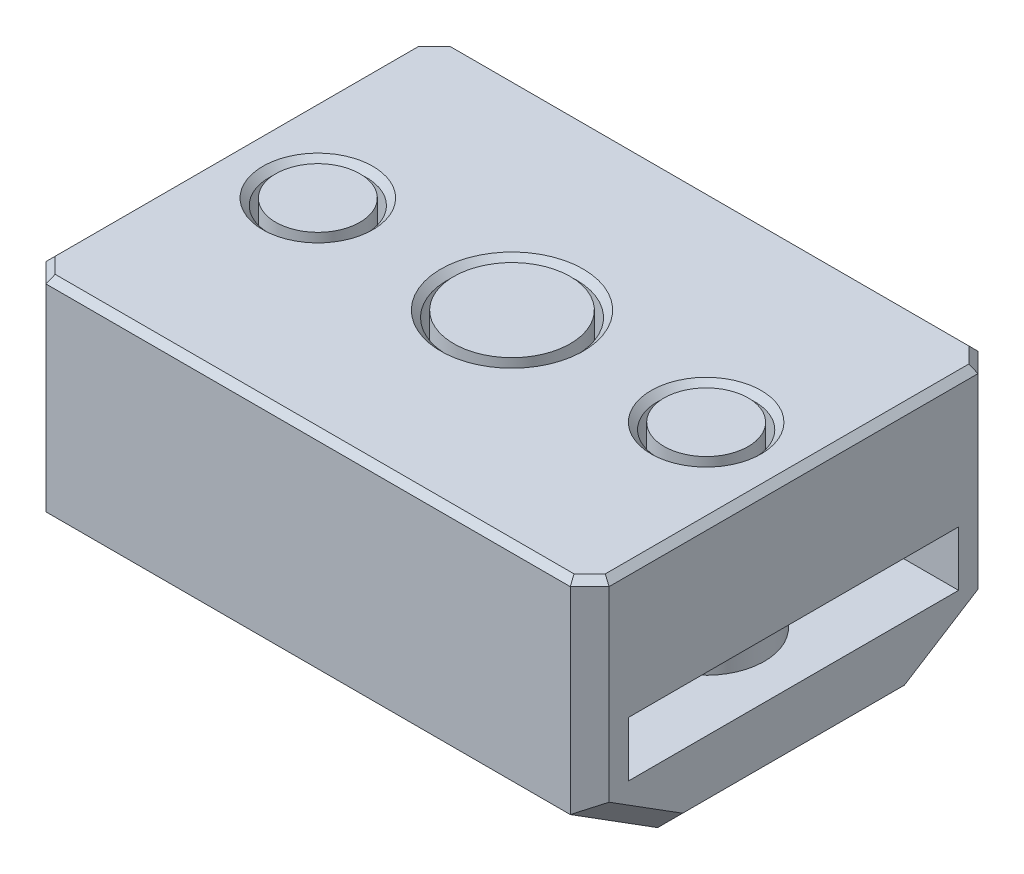
SolidWorks part; units mm, degrees
ref_plane "Front" through (0, 0, 0) normal (0, 0, 1) x (1, 0, 0)
ref_plane "Top" through (0, 0, 0) normal (0, 1, 0) x (1, 0, 0)
ref_plane "Right" through (0, 0, 0) normal (1, 0, 0) x (0, 0, -1)
sketch "Sketch1" plane through (0, 0, 0) normal (0, 1, 0) x (1, 0, 0)
  line L0 (9.5, 1.5) -> (9.5, -1.5) construction
  line L7 (10, -2) -> (14, -2) construction
  line L8 (14.5, -1.5) -> (14.5, 1.5) construction
  line L9 (14, 2) -> (10, 2) construction
  line L10 (9.5, 1.5) -> (9.5, -1.5)
  line L11 (10, -2) -> (14, -2)
  line L12 (14.5, -1.5) -> (14.5, 1.5)
  line L13 (14, 2) -> (10, 2)
  line L14 (-15.1, 2.5) -> (-15.1, -2.5)
  line L15 (-15.071, -2.571) -> (-12.571, -5.071)
  line L16 (-12.5, -5.1) -> (12.5, -5.1)
  line L17 (12.571, -5.071) -> (15.071, -2.571)
  line L18 (15.1, -2.5) -> (15.1, 2.5)
  line L19 (15.071, 2.571) -> (12.571, 5.071)
  line L20 (12.5, 5.1) -> (-12.5, 5.1)
  line L21 (-12.571, 5.071) -> (-15.071, 2.571)
  line L22 (-15.1, 2.5) -> (-15.1, -2.5)
  line L23 (-15.071, -2.571) -> (-12.571, -5.071)
  line L24 (-12.5, -5.1) -> (12.5, -5.1)
  line L25 (12.571, -5.071) -> (15.071, -2.571)
  line L26 (15.1, -2.5) -> (15.1, 2.5)
  line L27 (15.071, 2.571) -> (12.571, 5.071)
  line L28 (12.5, 5.1) -> (-12.5, 5.1)
  line L29 (-12.571, 5.071) -> (-15.071, 2.571)
  line L30 (-10, 2) -> (-14, 2) construction
  line L31 (-14.5, 1.5) -> (-14.5, -1.5) construction
  line L32 (-14, -2) -> (-10, -2) construction
  line L33 (-9.5, -1.5) -> (-9.5, 1.5) construction
  line L34 (-10, 2) -> (-14, 2)
  line L35 (-14.5, 1.5) -> (-14.5, -1.5)
  line L36 (-14, -2) -> (-10, -2)
  line L37 (-9.5, -1.5) -> (-9.5, 1.5)
  circle A0 centre (-6, 0) radius 1 construction
  circle A1 centre (6, 0) radius 1 construction
  circle A2 centre (0, 0) radius 1 construction
  circle A3 centre (-6, 0) radius 1
  circle A4 centre (6, 0) radius 1
  circle A5 centre (0, 0) radius 1
  arc A6 (9.5, -1.5) -> (10, -2) centre (10, -1.5) ccw construction
  arc A7 (14, -2) -> (14.5, -1.5) centre (14, -1.5) ccw construction
  arc A8 (-15.071, 2.571) -> (-15.1, 2.5) centre (-15.0029, 2.5018) ccw
  arc A9 (-15.1, -2.5) -> (-15.071, -2.571) centre (-15.0029, -2.5018) ccw
  arc A10 (-12.571, -5.071) -> (-12.5, -5.1) centre (-12.5018, -5.0029) ccw
  arc A11 (12.5, -5.1) -> (12.571, -5.071) centre (12.5018, -5.0029) ccw
  arc A12 (15.071, -2.571) -> (15.1, -2.5) centre (15.0029, -2.5018) ccw
  arc A13 (15.1, 2.5) -> (15.071, 2.571) centre (15.0029, 2.5018) ccw
  arc A14 (12.571, 5.071) -> (12.5, 5.1) centre (12.5018, 5.0029) ccw
  arc A15 (-12.5, 5.1) -> (-12.571, 5.071) centre (-12.5018, 5.0029) ccw
  arc A16 (-15.071, 2.571) -> (-15.1, 2.5) centre (-15.0029, 2.5018) ccw
  arc A17 (-15.1, -2.5) -> (-15.071, -2.571) centre (-15.0029, -2.5018) ccw
  arc A18 (-12.571, -5.071) -> (-12.5, -5.1) centre (-12.5018, -5.0029) ccw
  arc A19 (12.5, -5.1) -> (12.571, -5.071) centre (12.5018, -5.0029) ccw
  arc A20 (15.071, -2.571) -> (15.1, -2.5) centre (15.0029, -2.5018) ccw
  arc A21 (15.1, 2.5) -> (15.071, 2.571) centre (15.0029, 2.5018) ccw
  arc A22 (12.571, 5.071) -> (12.5, 5.1) centre (12.5018, 5.0029) ccw
  arc A23 (-12.5, 5.1) -> (-12.571, 5.071) centre (-12.5018, 5.0029) ccw
  arc A24 (14.5, 1.5) -> (14, 2) centre (14, 1.5) ccw construction
  arc A25 (10, 2) -> (9.5, 1.5) centre (10, 1.5) ccw construction
  arc A26 (9.5, -1.5) -> (10, -2) centre (10, -1.5) ccw
  arc A27 (14, -2) -> (14.5, -1.5) centre (14, -1.5) ccw
  arc A28 (14.5, 1.5) -> (14, 2) centre (14, 1.5) ccw
  arc A29 (10, 2) -> (9.5, 1.5) centre (10, 1.5) ccw
  arc A30 (-14, 2) -> (-14.5, 1.5) centre (-14, 1.5) ccw construction
  arc A31 (-14.5, -1.5) -> (-14, -2) centre (-14, -1.5) ccw construction
  arc A32 (-10, -2) -> (-9.5, -1.5) centre (-10, -1.5) ccw construction
  arc A33 (-9.5, 1.5) -> (-10, 2) centre (-10, 1.5) ccw construction
  arc A34 (-14, 2) -> (-14.5, 1.5) centre (-14, 1.5) ccw
  arc A35 (-14.5, -1.5) -> (-14, -2) centre (-14, -1.5) ccw
  arc A36 (-10, -2) -> (-9.5, -1.5) centre (-10, -1.5) ccw
  arc A37 (-9.5, 1.5) -> (-10, 2) centre (-10, 1.5) ccw
  point P0 (0, 0)
  dimension "D1" = 0
sketch "Sketch3" plane through (0, 0, 0) normal (0, 1, 0) x (1, 0, 0)
  line L0 (-8.7, 6.3) -> (-8.7, -6.3)
  line L1 (8.7, 6.3) -> (8.7, -6.3)
  line L2 (-8.7, 6.3) -> (8.7, 6.3)
  line L3 (8.7, -6.3) -> (-8.7, -6.3)
  line L4 (12.5, 5.1) -> (-12.5, 5.1) construction
  line L5 (7.5, 0) -> (8.7, 0) construction
  circle A0 centre (-6, 0) radius 1.5
  circle A1 centre (0, 0) radius 2
  circle A2 centre (6, 0) radius 1.5
  point P11 (-8.7, 0)
  point P14 (8.7, 0)
  point P17 (0, 6.3)
  dimension "D1" = 3
  dimension "D2" = 4
  dimension "D3" = 1.2
  dimension "D4" = 1.2
  dimension "D5" = 12.6
extrude "Boss-Extrude1" add sketch "Sketch3" along normal blind 4
sketch "Sketch4" plane through (0, 4, 0) normal (0, 1, 0) x (1, 0, 0)
  circle A0 centre (6, 0) radius 1.5 construction
  circle A1 centre (-6, 0) radius 1.5 construction
  circle A2 centre (6, 0) radius 1.5
  circle A3 centre (-6, 0) radius 1.5
  circle A4 centre (-6, 0) radius 1
  circle A5 centre (6, 0) radius 1
  dimension "D1" = 2
extrude "Boss-Extrude2" add sketch "Sketch4" against normal up to surface (0.8 mm away) from offset 3.2 up to face at (0, 0, 2) offset against normal yes
sketch "Sketch11" plane through (0, 0.8, 0) normal (0, 1, 0) x (1, 0, 0)
  circle A3 centre (-6, 0) radius 1.3
  circle A4 centre (-6, 0) radius 1.3
  circle A6 centre (6, 0) radius 1.3
  dimension "D1" = 0.2
extrude "Boss-Extrude7" add sketch "Sketch11" along normal up to surface (3 mm away) from offset 0.2 separate body up to face at (0, 4, 0)
sketch "Sketch5" plane through (0, 0, 0) normal (0, -1, 0) x (1, 0, 0)
  line L0 (8.7, 6.3) -> (8.7, -6.3) construction
  line L1 (-8.7, 6.3) -> (8.7, 6.3)
  line L2 (-8.7, 6.3) -> (-8.7, 5.1)
  line L3 (-8.7, 5.1) -> (8.7, 5.1)
  line L4 (8.7, 6.3) -> (8.7, 5.1)
  line L5 (-8.7, -6.3) -> (-8.7, 6.3) construction
  line L6 (8.7, -6.3) -> (-8.7, -6.3)
  line L7 (8.7, -6.3) -> (8.7, -5.1)
  line L8 (8.7, -5.1) -> (-8.7, -5.1)
  line L9 (-8.7, -6.3) -> (-8.7, -5.1)
  line L10 (12.5, -5.1) -> (-12.5, -5.1) construction
  dimension "D1" = 1.2
extrude "Boss-Extrude3" add sketch "Sketch5" along normal blind 1.7
sketch "Sketch8" plane through (0, -1.7, 0) normal (0, -1, 0) x (1, 0, 0)
  line L1 (2.3094, 0) -> (1.1547, 2) construction
  line L2 (1.1547, 2) -> (-1.1547, 2) construction
  line L3 (-1.1547, 2) -> (-2.3094, 0) construction
  line L4 (-2.3094, 0) -> (-1.1547, -2) construction
  line L5 (-1.1547, -2) -> (1.1547, -2) construction
  line L6 (1.1547, -2) -> (2.3094, 0) construction
  line L7 (-8.7, 6.3) -> (8.7, 6.3)
  line L8 (-8.7, 6.3) -> (-8.7, -6.3)
  line L9 (-8.7, -6.3) -> (8.7, -6.3)
  line L10 (8.7, 6.3) -> (8.7, -6.3)
  circle A0 centre (0, 0) radius 2 construction
  circle A1 centre (6, 0) radius 1 construction
  circle A2 centre (-6, 0) radius 1 construction
  circle A3 centre (6, 0) radius 1
  circle A4 centre (-6, 0) radius 1
  circle A7 centre (0, 0) radius 1
  dimension "D1" = 4
extrude "Boss-Extrude5" add sketch "Sketch8" along normal blind 0.6
sketch "Sketch12" plane through (0, -2.3, 0) normal (0, -1, 0) x (1, 0, 0)
  line L0 (-8.7, 6.3) -> (-8.7, -6.3) construction
  line L1 (-8.7, -6.3) -> (8.7, -6.3) construction
  line L2 (8.7, 6.3) -> (8.7, -6.3) construction
  line L3 (-8.7, 6.3) -> (8.7, 6.3) construction
  line L4 (-8.7, 6.3) -> (-8.7, -6.3)
  line L5 (-8.7, -6.3) -> (8.7, -6.3)
  line L6 (8.7, 6.3) -> (8.7, -6.3)
  line L7 (-8.7, 6.3) -> (8.7, 6.3)
  line L8 (-1.1547, 2) -> (-2.3094, 0) construction
  line L9 (-2.3094, 0) -> (-1.1547, -2) construction
  line L10 (-1.1547, -2) -> (1.1547, -2) construction
  line L11 (1.1547, -2) -> (2.3094, 0) construction
  line L12 (2.3094, 0) -> (1.1547, 2) construction
  line L13 (1.1547, 2) -> (-1.1547, 2) construction
  line L14 (-1.1547, 2) -> (-2.3094, 0)
  line L15 (-2.3094, 0) -> (-1.1547, -2)
  line L16 (-1.1547, -2) -> (1.1547, -2)
  line L17 (1.1547, -2) -> (2.3094, 0)
  line L18 (2.3094, 0) -> (1.1547, 2)
  line L19 (1.1547, 2) -> (-1.1547, 2)
  circle A0 centre (6, 0) radius 1 construction
  circle A1 centre (-6, 0) radius 1 construction
  circle A2 centre (6, 0) radius 1
  circle A3 centre (-6, 0) radius 1
extrude "Boss-Extrude8" add sketch "Sketch12" along normal blind 1.7
sketch "Sketch13" plane through (-8.7, 0, 0) normal (-1, 0, 0) x (0, 0, 1)
  line L0 (6.3, -4) -> (3.6, -4)
  line L1 (6.3, -4) -> (-6.3, -4) construction
  line L2 (3.6, -4) -> (6.3, -2.3)
  line L3 (6.3, 4) -> (6.3, -4) construction
  line L4 (6.3, -2.3) -> (6.3, -4)
  line L5 (-6.3, -4) -> (-6.3, -2.3)
  line L6 (-6.3, 4) -> (-6.3, -4) construction
  line L7 (-6.3, -2.3) -> (-3.6, -4)
  line L8 (-3.6, -4) -> (-6.3, -4)
  line L9 (5.1, -1.7) -> (-5.1, -1.7) construction
  dimension "D1" = 1.6
  dimension "D2" = 0.6
extrude "Cut-Extrude1" cut sketch "Sketch13" against normal through all both and the other way through all
chamfer "Chamfer1" distance 0.6 angle 45 10 edges at (8.7, 0.85, 6.3) (-8.7, 0.85, 6.3) (8.7, 0.85, -6.3) (-8.7, 0.85, -6.3) (8.7, -3.15, 4.95) (8.7, -4, 0) (8.7, -3.15, -4.95) (-8.7, -3.15, 4.95) (-8.7, -4, 0) (-8.7, -3.15, -4.95)
chamfer "Chamfer3" distance 0.2 angle 45 11 edges at (6, 4, 1.5) (0, 4, 2) (-6, 4, 1.5) (-8.4, 4, 6) (-8.7, 4, 0) (-8.4, 4, -6) (0, 4, -6.3) (8.4, 4, -6) (8.7, 4, 0) (8.4, 4, 6) (0, 4, 6.3)
sketch "Sketch14" plane through (0, -1.7, 0) normal (0, 1, 0) x (1, 0, 0)
  circle A2 centre (0, 0) radius 1.8
  circle A3 centre (0, 0) radius 1.8
  dimension "D1" = 0.2
extrude "Boss-Extrude9" add sketch "Sketch14" along normal up to surface (5.5 mm away) from offset 0.2 separate body up to face at (6, 4, -1.7)
sketch "Sketch15" plane through (0, -1.7, 0) normal (0, 1, 0) x (1, 0, 0)
  circle A0 centre (-6, 0) radius 1 construction
  circle A1 centre (6, 0) radius 1 construction
  circle A2 centre (-6, 0) radius 1
  circle A3 centre (6, 0) radius 1
  circle A4 centre (-6, 0) radius 1.8
  circle A5 centre (6, 0) radius 1.8
  dimension "D1" = 0.8
extrude "Boss-Extrude10" add sketch "Sketch15" along normal offset from surface (1.3 mm away) 0.2 from offset 0.2 separate body up to face at (0, 0, 2)
